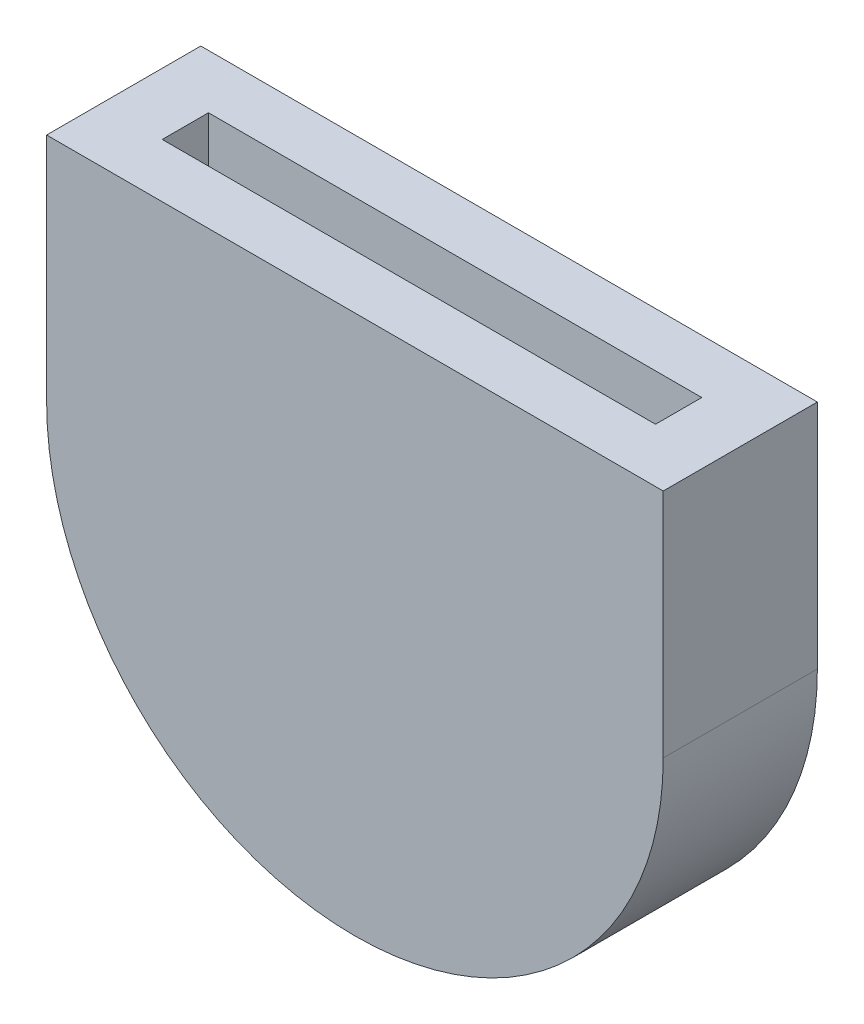
SolidWorks part; units mm, degrees
ref_plane "前视基准面" through (0, 0, 0) normal (0, 0, 1) x (1, 0, 0)
ref_plane "上视基准面" through (0, 0, 0) normal (0, 1, 0) x (1, 0, 0)
ref_plane "右视基准面" through (0, 0, 0) normal (1, 0, 0) x (0, 0, -1)
sketch "草图1" plane through (0, 0, 0) normal (0, 0, 1) x (1, 0, 0)
  line L0 (-20, 0) -> (-20, 15)
  line L1 (-20, 15) -> (20, 15)
  line L2 (20, 15) -> (20, 0)
  arc A1 (-20, 0) -> (20, 0) centre (0, 0) ccw
  dimension "D1" = 15
  dimension "D2" = 40
extrude "凸台-拉伸1" add sketch "草图1" along normal mid plane 10
sketch "草图2" plane through (0, 0, 0) normal (0, 0, 1) x (1, 0, 0)
  line L0 (-16, 0) -> (-16, 15)
  line L1 (20, 15) -> (-20, 15) construction
  line L2 (16, 0) -> (16, 15)
  line L3 (-16, 15) -> (16, 15)
  arc A0 (-16, 0) -> (16, 0) centre (0, 0) ccw
  dimension "D1" = 32
extrude "切除-拉伸2" cut sketch "草图2" against normal mid plane 3
